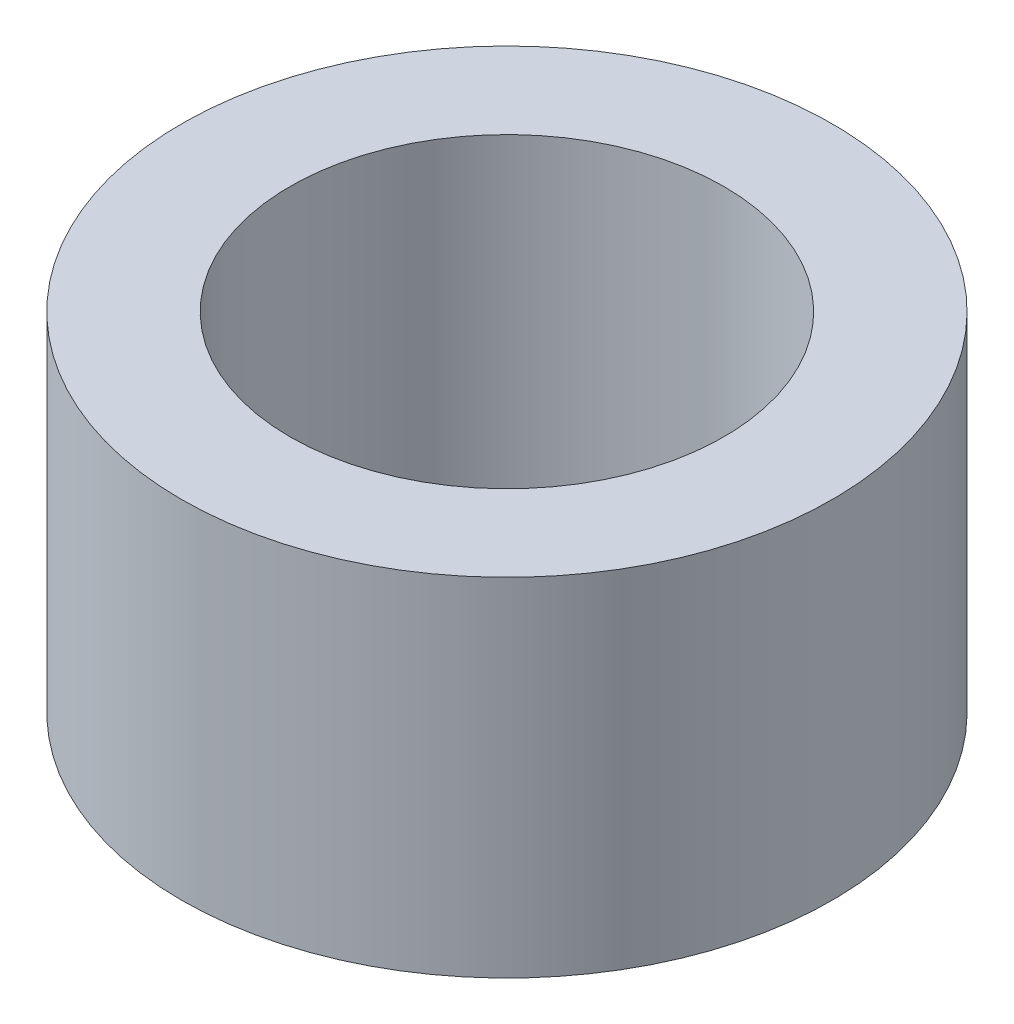
SolidWorks part; units mm, degrees
ref_plane "正面" through (0, 0, 0) normal (0, 0, 1) x (1, 0, 0)
ref_plane "平面" through (0, 0, 0) normal (0, 1, 0) x (1, 0, 0)
ref_plane "右側面" through (0, 0, 0) normal (1, 0, 0) x (0, 0, -1)
sketch "ｽｹｯﾁ1" plane through (0, 0, 0) normal (0, 1, 0) x (1, 0, 0)
  circle A0 centre (0, 0) radius 3
  circle A1 centre (0, 0) radius 4.5
  dimension "D1" = 6
  dimension "D2" = 1.5
extrude "ﾎﾞｽ - 押し出し1" add sketch "ｽｹｯﾁ1" along normal blind 4.8
